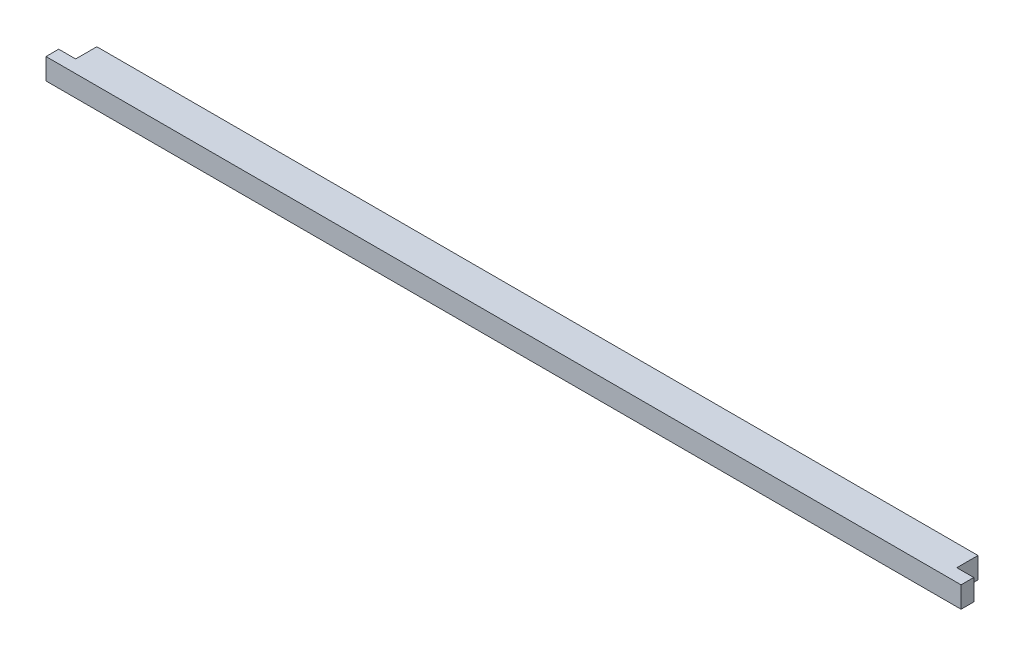
SolidWorks part; units mm, degrees
ref_plane "Front Plane" through (0, 0, 0) normal (0, 0, 1) x (1, 0, 0)
ref_plane "Top Plane" through (0, 0, 0) normal (0, 1, 0) x (1, 0, 0)
ref_plane "Right Plane" through (0, 0, 0) normal (1, 0, 0) x (0, 0, -1)
sketch "Sketch1" plane through (0, 0, 0) normal (0, 1, 0) x (1, 0, 0)
  line L1 (0, 0) -> (432, 0)
  line L2 (0, 0) -> (0, 16)
  line L3 (0, 16) -> (432, 16)
  line L4 (432, 0) -> (432, 16)
  line L7 (0, 8) -> (10, 8)
  line L8 (10, 16) -> (10, 8)
  line L11 (432, 8) -> (422, 8)
  line L12 (422, 16) -> (422, 8)
  dimension "D1" = 432
  dimension "D2" = 16
  dimension "D3" = 10
  dimension "D4" = 10
  dimension "D5" = 8
  dimension "D6" = 8
extrude "Boss-Extrude2" add sketch "Sketch1" along normal blind 10 contours L2 L1 L4 L3
sketch "Sketch2" plane through (0, 10, 0) normal (0, 1, 0) x (1, 0, 0)
  line L0 (424, 16) -> (424, 6)
  line L1 (0, 16) -> (8, 16)
  line L2 (0, 16) -> (0, 6)
  line L3 (0, 6) -> (8, 6)
  line L4 (8, 16) -> (8, 6)
  line L5 (424, 16) -> (432, 16)
  line L6 (432, 16) -> (432, 6)
  line L7 (424, 6) -> (432, 6)
  line L8 (432, 0) -> (432, 16) construction
  dimension "D1" = 8
  dimension "D2" = 10
  dimension "D4" = 0
  dimension "D3" = 2
extrude "Cut-Extrude3" cut sketch "Sketch2" against normal blind 10
